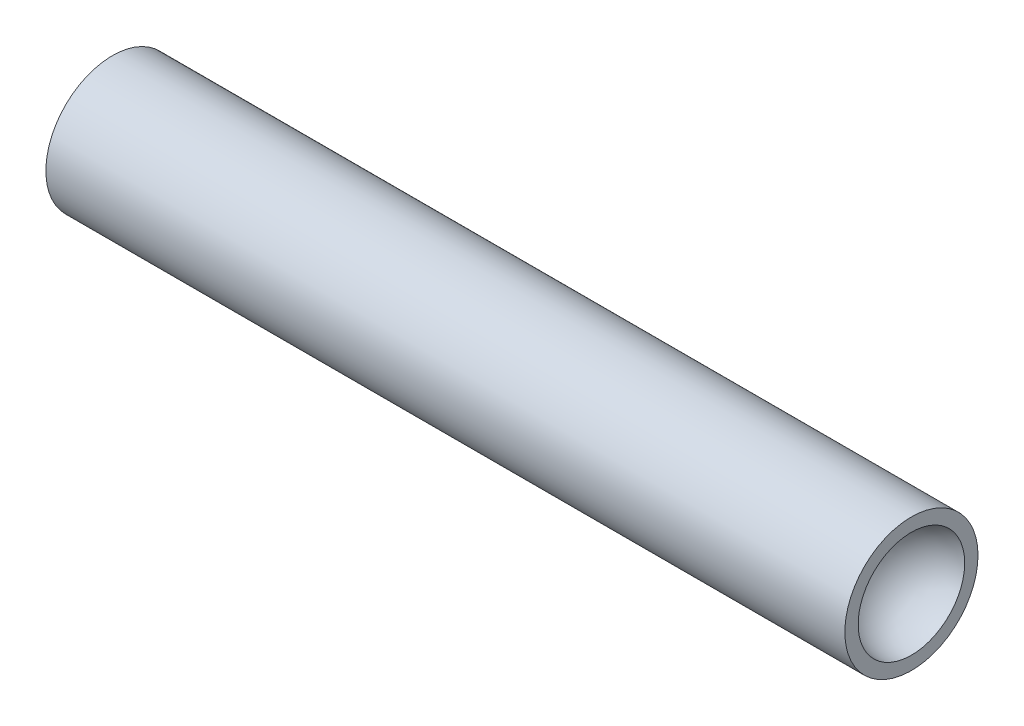
SolidWorks part; units mm, degrees
ref_plane "Front Plane" through (0, 0, 0) normal (0, 0, 1) x (1, 0, 0)
ref_plane "Top Plane" through (0, 0, 0) normal (0, 1, 0) x (1, 0, 0)
ref_plane "Right Plane" through (0, 0, 0) normal (1, 0, 0) x (0, 0, -1)
sketch "Sketch1" plane through (0, 0, 0) normal (1, 0, 0) x (0, 0, -1)
  circle A0 centre (0, 0) radius 25
  dimension "D1" = 50
extrude "Boss-Extrude1" add sketch "Sketch1" along normal blind 300
ref_plane "Plane1" through (301.016, 0, 0) normal (1, 0, 0) x (0, 0, -1)
sketch "Sketch2" plane through (300, 0, 0) normal (1, 0, 0) x (0, 0, -1)
  line L0 (-20, 0) -> (20, 0)
  arc A2 (-20, 0) -> (20, 0) centre (0, 0) cw
  dimension "D1" = 20
revolve "Cut-Revolve3" cut sketch "Sketch2" angle 360 about L0
sketch "Sketch3" plane through (0, 0, 0) normal (-1, 0, 0) x (0, 0, 1)
  circle A0 centre (0, 0) radius 20
  dimension "D1" = 40
extrude "Cut-Extrude1" cut sketch "Sketch3" against normal blind 200
ref_plane "Plane2" through (160, 0, 0) normal (1, 0, 0) x (0, 0, -1)
sketch "Sketch4" plane through (160, 0, 0) normal (1, 0, 0) x (0, 0, -1)
  circle A0 centre (0, 0) radius 25 construction
  circle A1 centre (0, 0) radius 25
